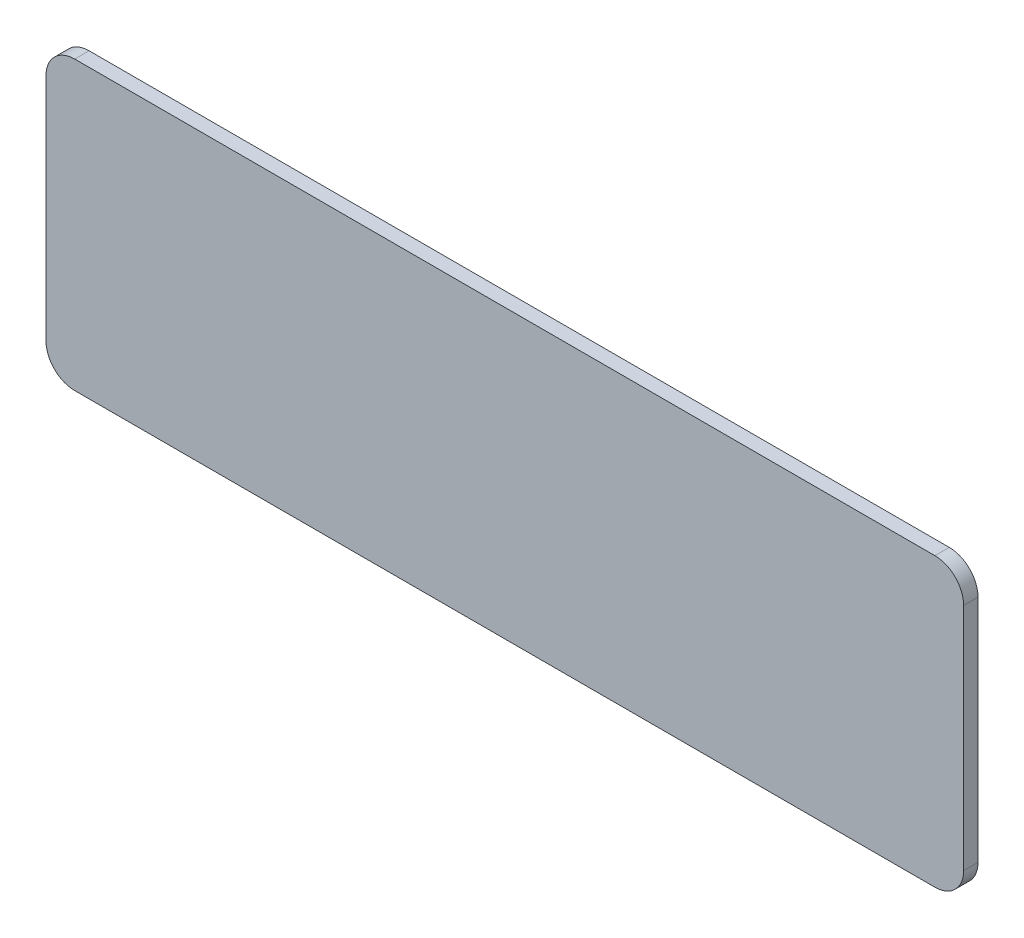
SolidWorks part; units mm, degrees
ref_plane "Front Plane" through (0, 0, 0) normal (0, 0, 1) x (1, 0, 0)
ref_plane "Top Plane" through (0, 0, 0) normal (0, 1, 0) x (1, 0, 0)
ref_plane "Right Plane" through (0, 0, 0) normal (1, 0, 0) x (0, 0, -1)
sketch "Sketch1" plane through (0, 0, 0) normal (0, 0, 1) x (1, 0, 0)
  line L1 (419.14, 100) -> (-180, 100)
  line L2 (439.14, 80) -> (439.14, -80)
  line L3 (419.14, -100) -> (-180, -100)
  line L4 (-200, 80) -> (-200, -80)
  arc A0 (419.14, 100) -> (439.14, 80) centre (419.14, 80) cw
  arc A1 (439.14, -80) -> (419.14, -100) centre (419.14, -80) cw
  arc A2 (-180, -100) -> (-200, -80) centre (-180, -80) cw
  arc A3 (-180, 100) -> (-200, 80) centre (-180, 80) ccw
  point P0 (0, 0)
  point P10 (439.14, -100)
  point P13 (-200, -100)
  point P16 (-200, 100)
  dimension "D3" = 20
  dimension "D1" = 639.14
  dimension "D2" = 200
extrude "Boss-Extrude1" add sketch "Sketch1" along normal blind 10
